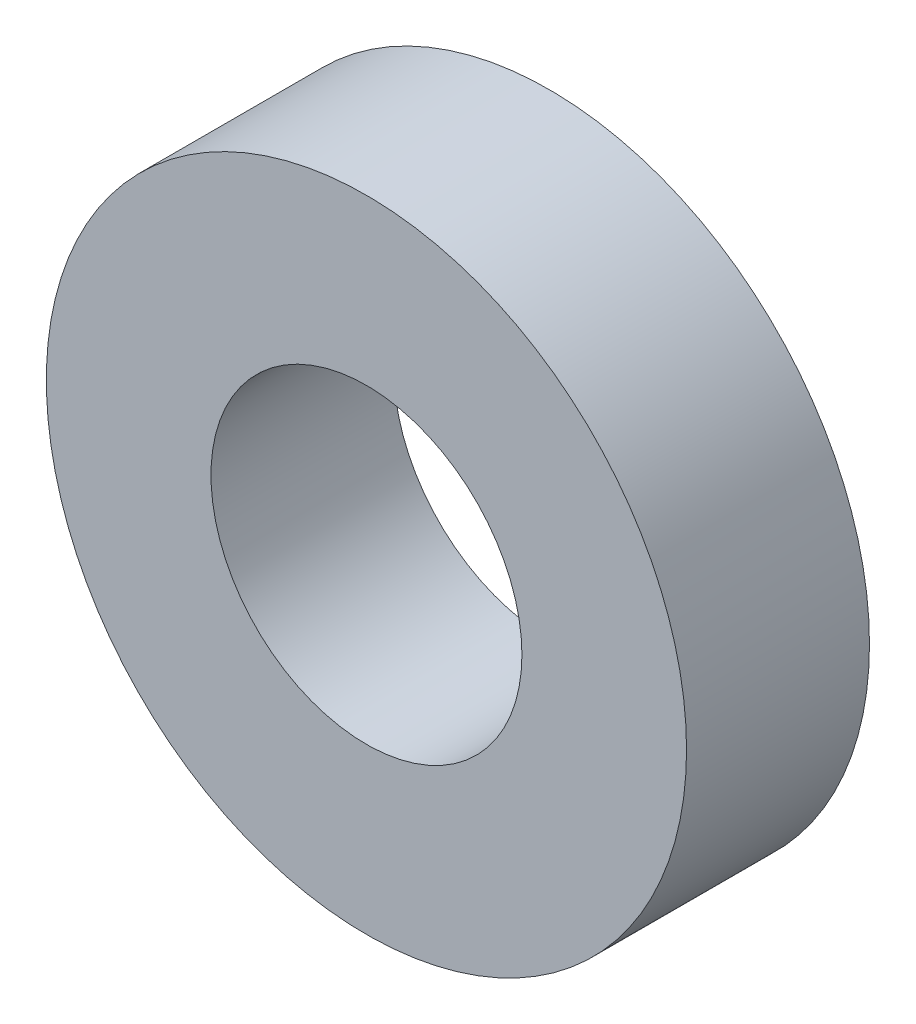
SolidWorks part; units mm, degrees
ref_plane "Front Plane" through (0, 0, 0) normal (0, 0, 1) x (1, 0, 0)
ref_plane "Top Plane" through (0, 0, 0) normal (0, 1, 0) x (1, 0, 0)
ref_plane "Right Plane" through (0, 0, 0) normal (1, 0, 0) x (0, 0, -1)
sketch "M3 clearance profile" plane through (0, 0, 0) normal (0, 0, 1) x (1, 0, 0)
  circle A0 centre (0, 0) radius 3.5
  circle A1 centre (0, 0) radius 1.7
extrude "M3 clearance" add sketch "M3 clearance profile" along normal blind 2
